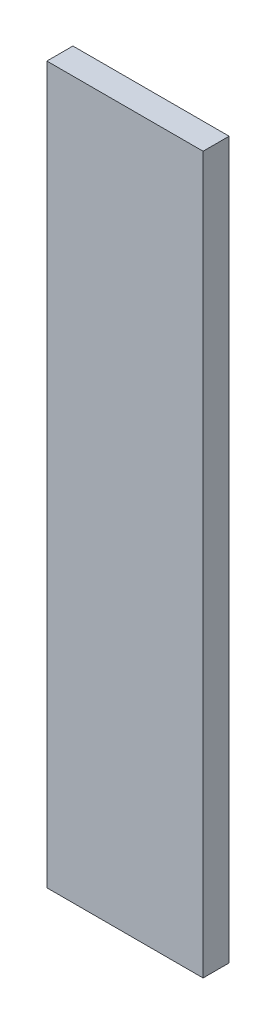
SolidWorks part; units mm, degrees
ref_plane "Front Plane" through (0, 0, 0) normal (0, 0, 1) x (1, 0, 0)
ref_plane "Top Plane" through (0, 0, 0) normal (0, 1, 0) x (1, 0, 0)
ref_plane "Right Plane" through (0, 0, 0) normal (1, 0, 0) x (0, 0, -1)
sketch "Szkic1" plane through (0, 0, 0) normal (0, 0, 1) x (1, 0, 0)
  line L0 (6, 27.5) -> (-6, -27.5) construction
  line L1 (-6, 27.5) -> (6, 27.5)
  line L2 (-6, 27.5) -> (-6, -27.5)
  line L3 (-6, -27.5) -> (6, -27.5)
  line L4 (6, 27.5) -> (6, -27.5)
  dimension "D1" = 12
  dimension "D2" = 55
extrude "Dodanie-wyciągnięcie1" add sketch "Szkic1" along normal blind 2
